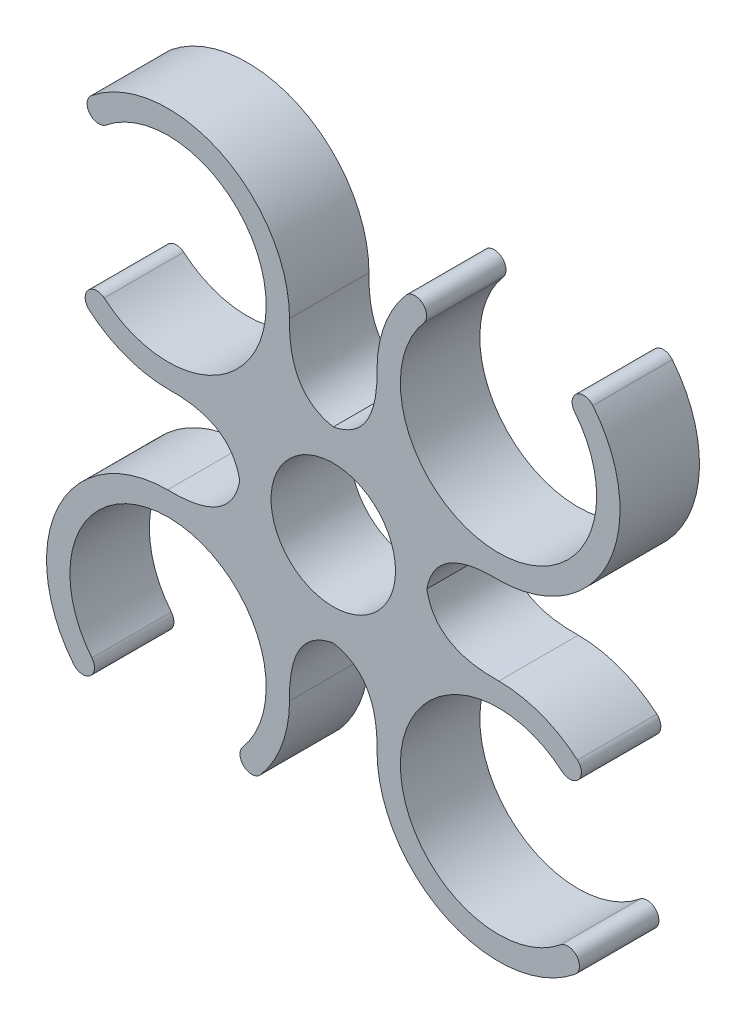
SolidWorks part; units mm, degrees
ref_plane "Plan de face" through (0, 0, 0) normal (0, 0, 1) x (1, 0, 0)
ref_plane "Plan de dessus" through (0, 0, 0) normal (0, 1, 0) x (1, 0, 0)
ref_plane "Plan de droite" through (0, 0, 0) normal (1, 0, 0) x (0, 0, -1)
sketch "Esquisse2" plane through (0, 0, 0) normal (0, 0, 1) x (1, 0, 0)
  arc A20 (-41.9703, 58.2889) -> (-45.1061, 62.1833) centre (-43.5301, 60.2426) cw
  arc A21 (-45.5982, 22.2264) -> (-42.3689, 26.0444) centre (-43.9425, 24.1007) cw
  arc A22 (-28.7962, 16) -> (-45.5982, 22.2264) centre (-28.7158, 42.0003) cw
  arc A23 (-2.716, 42.0802) -> (-45.1061, 62.1833) centre (-28.7158, 42.0003) ccw
  arc A24 (-42.3689, 26.0444) -> (-7.8144, 39.9671) centre (-28.7158, 42.0003) ccw
  arc A25 (-7.8144, 39.9671) -> (-41.9703, 58.2889) centre (-28.7158, 42.0003) ccw
  arc A26 (-45.0049, -41.9703) -> (-48.8992, -45.1061) centre (-46.9585, -43.5301) cw
  arc A27 (-8.9424, -45.5982) -> (-12.7603, -42.3689) centre (-10.8166, -43.9425) cw
  arc A28 (-2.716, -28.7962) -> (-8.9424, -45.5982) centre (-28.7162, -28.7158) cw
  arc A29 (-28.7961, -2.716) -> (-48.8992, -45.1061) centre (-28.7162, -28.7158) ccw
  circle A30 centre (6.642, 6.642) radius 13.3159
  arc A31 (-12.7603, -42.3689) -> (-26.683, -7.8144) centre (-28.7162, -28.7158) ccw
  arc A32 (-26.683, -7.8144) -> (-45.0049, -41.9703) centre (-28.7162, -28.7158) ccw
  arc A33 (55.2543, -45.0049) -> (58.3901, -48.8992) centre (56.8142, -46.9585) cw
  arc A34 (58.8822, -8.9424) -> (55.653, -12.7603) centre (57.2266, -10.8166) cw
  arc A35 (42.0802, -2.716) -> (58.8822, -8.9424) centre (41.9998, -28.7162) cw
  arc A36 (16, -28.7961) -> (58.3901, -48.8992) centre (41.9998, -28.7162) ccw
  arc A37 (55.653, -12.7603) -> (21.0985, -26.683) centre (41.9998, -28.7162) ccw
  arc A38 (21.0985, -26.683) -> (55.2543, -45.0049) centre (41.9998, -28.7162) ccw
  arc A39 (58.2889, 55.2543) -> (62.1833, 58.3901) centre (60.2426, 56.8142) cw
  arc A40 (22.2264, 58.8822) -> (26.0443, 55.653) centre (24.1007, 57.2266) cw
  arc A41 (16, 42.0802) -> (22.2264, 58.8822) centre (42.0003, 41.9998) cw
  arc A42 (42.0802, 16) -> (62.1833, 58.3901) centre (42.0003, 41.9998) ccw
  arc A43 (26.0443, 55.653) -> (39.9671, 21.0985) centre (42.0003, 41.9998) ccw
  arc A44 (39.9671, 21.0985) -> (58.2889, 55.2543) centre (42.0003, 41.9998) ccw
  spline S0 degree 2 poles (-28.7961, -2.716) (-15.2077, -3.0351) (-13.3737, 6.6421) knots 0 0 0 1 1 1
  spline S1 degree 2 poles (-2.716, -28.7962) (-3.0352, -15.2078) (6.642, -13.3737) knots 0 0 0 1 1 1
  spline S2 degree 2 poles (-2.716, 42.0802) (-3.0351, 28.4917) (6.6421, 26.6578) knots 0 0 0 1 1 1
  spline S3 degree 2 poles (16, -28.7961) (16.3192, -15.2077) (6.642, -13.3737) knots 0 0 0 1 1 1
  spline S4 degree 2 poles (42.0802, -2.716) (28.4918, -3.0352) (26.6577, 6.642) knots 0 0 0 1 1 1
  spline S5 degree 2 poles (42.0802, 16) (28.4917, 16.3192) (26.6577, 6.642) knots 0 0 0 1 1 1
  spline S6 degree 2 poles (16, 42.0802) (16.3192, 28.4918) (6.6421, 26.6578) knots 0 0 0 1 1 1
  spline S8 degree 2 poles (-28.7962, 16) (-15.2078, 16.3192) (-13.3737, 6.6421) knots 0 0 0 1 1 1
  point P5 (6.642, 6.642)
  point P12 (6.642, 6.642)
  point P65 (6.642, 6.642)
  dimension "D1" = 4
extrude "Boss.-Extru.1" add sketch "Esquisse2" along normal blind 17
